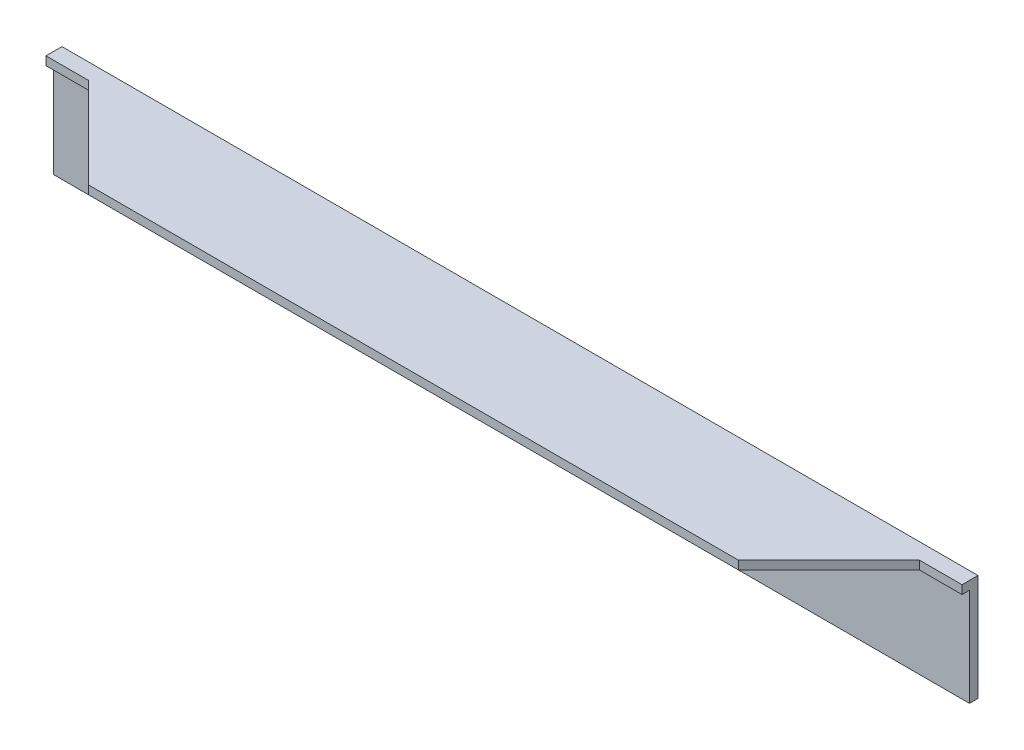
SolidWorks part; units mm, degrees
ref_plane "前视基准面" through (0, 0, 0) normal (0, 0, 1) x (1, 0, 0)
ref_plane "上视基准面" through (0, 0, 0) normal (0, 1, 0) x (1, 0, 0)
ref_plane "右视基准面" through (0, 0, 0) normal (1, 0, 0) x (0, 0, -1)
sketch "草图1" plane through (0, 0, 0) normal (0, 0, 1) x (1, 0, 0)
  line L0 (-1000, 0) -> (49000, 0) construction
  line L1 (-430, 0) -> (430, 0)
  line L2 (430, 0) -> (430, 100)
  line L3 (430, 100) -> (-430, 100)
  line L4 (0, -1000) -> (0, 49000) construction
  line L5 (390, -944.3218) -> (390, 49055.6782) construction
  line L6 (-723.7245, 40) -> (49276.2755, 40) construction
  line L7 (310, -974.291) -> (310, 49025.709) construction
  line L8 (-430, 0) -> (-430, 100)
  point P26 (0, 0)
  point P27 (0, 100)
  dimension "D1" = 430
  dimension "D2" = 100
  dimension "D4" = 40
  dimension "D5" = 60
  dimension "D7" = 80
extrude "凸台-拉伸1" add sketch "草图1" along normal blind 8
sketch "草图2" plane through (0, 0, 8) normal (0, 0, 1) x (1, 0, 0)
  line L1 (-430, 100) -> (430, 100)
  line L2 (-430, 100) -> (-430, 92)
  line L3 (-430, 92) -> (430, 92)
  line L4 (430, 100) -> (430, 92)
  point P0 (-430, 100)
  dimension "D1" = 860
  dimension "D2" = 8
extrude "凸台-拉伸2" add sketch "草图2" along normal blind 92
sketch "草图3" plane through (0, 100, 0) normal (0, 1, 0) x (1, 0, 0)
  line L0 (-390, -1024.4681) -> (-390, 48975.5319) construction
  line L1 (-430, -100) -> (-430, 0) construction
  dimension "D1" = 40
sketch "草图4" plane through (0, 100, 0) normal (0, 1, 0) x (1, 0, 0)
  line L0 (-1254.233, -15) -> (48745.767, -15) construction
  line L1 (430, 0) -> (-430, 0) construction
  line L2 (-390, -201024.4681) -> (-390, 248975.5319) construction
  line L3 (-390, -15) -> (34965.3391, -35370.3391) construction
  line L4 (430, -100) -> (-430, -100) construction
  line L5 (-430, -100) -> (-430, 0) construction
  line L6 (-430, -15) -> (-390, -15)
  line L7 (-390, -15) -> (-305, -100)
  line L8 (-305, -100) -> (-430, -100)
  line L9 (-430, -100) -> (-430, -15)
  point P4 (-390, -15)
  point P9 (-305, -100)
  point P10 (-430, -15)
  dimension "D1" = 15
  dimension "D2" = 45
extrude "切除-拉伸1" cut sketch "草图4" against normal through all
mirror "镜向1" about plane through (0, 0, 0) normal (1, 0, 0) of "切除-拉伸1"
